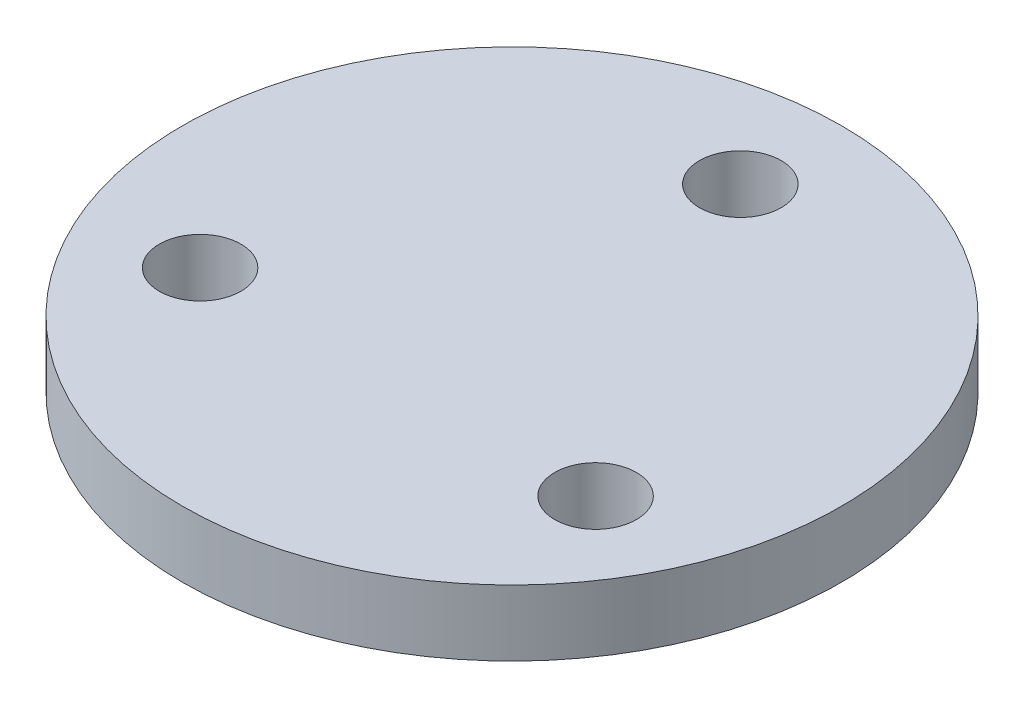
SolidWorks part; units mm, degrees
ref_plane "Front Plane" through (0, 0, 0) normal (0, 0, 1) x (1, 0, 0)
ref_plane "Top Plane" through (0, 0, 0) normal (0, 1, 0) x (1, 0, 0)
ref_plane "Right Plane" through (0, 0, 0) normal (1, 0, 0) x (0, 0, -1)
sketch "Sketch1" plane through (0, 0, 0) normal (0, 1, 0) x (1, 0, 0)
  line L1 (0, 21.997) -> (-19.05, -10.9985) construction
  line L2 (-19.05, -10.9985) -> (19.05, -10.9985) construction
  line L3 (19.05, -10.9985) -> (0, 21.997) construction
  circle A0 centre (0, 0) radius 21.997 construction
  circle A1 centre (0, 21.997) radius 3.937
  circle A2 centre (19.05, -10.9985) radius 3.937
  circle A3 centre (0, 0) radius 21.997 construction
  circle A4 centre (-19.05, -10.9985) radius 3.937
  circle A5 centre (0, 0) radius 21.997 construction
  circle A6 centre (0, 0) radius 31.75
  point P16 (0, 0)
  dimension "D2" = 7.874
  dimension "D4" = 63.5
  dimension "D1" = 38.1
  dimension "D3" = 3
extrude "Boss-Extrude1" add sketch "Sketch1" along normal blind 6.35
